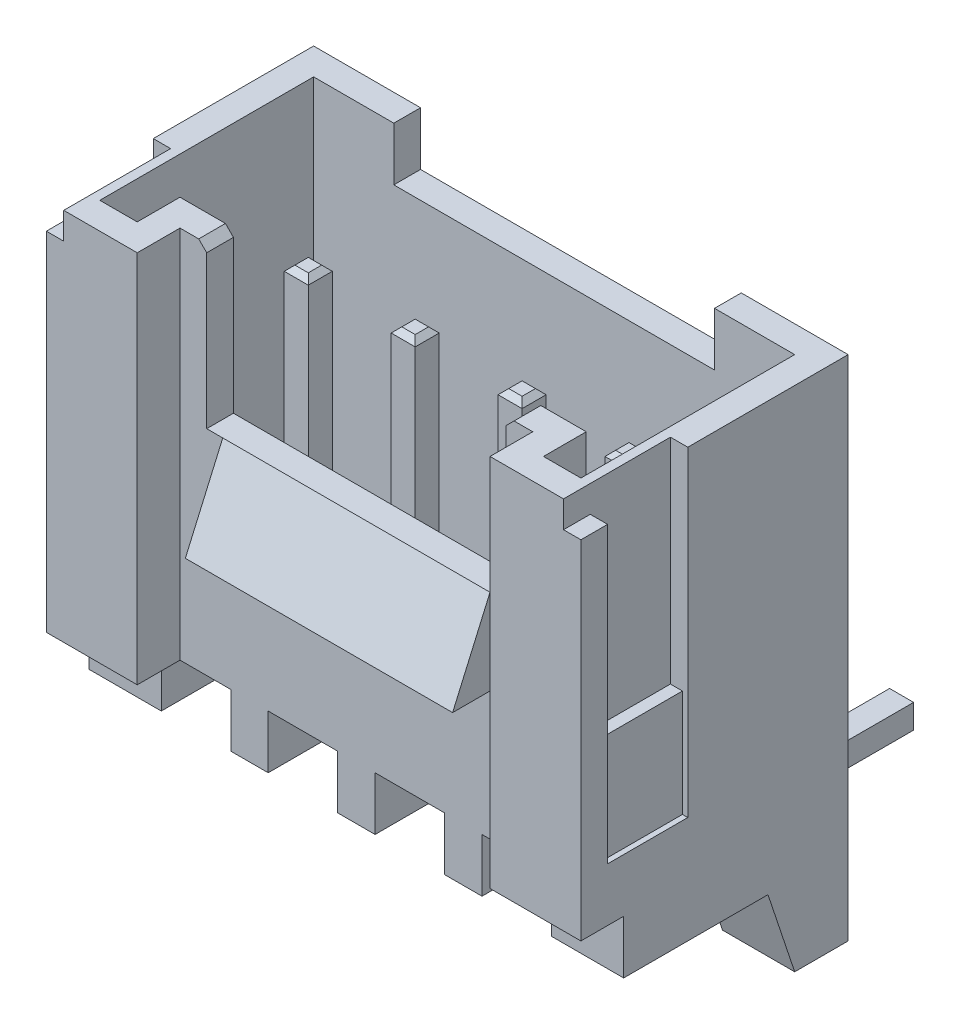
SolidWorks part; units mm, degrees
material "ABS"
ref_plane "Plan de face" through (0, 0, 0) normal (0, 0, 1) x (1, 0, 0)
ref_plane "Plan de dessus" through (0, 0, 0) normal (0, 1, 0) x (1, 0, 0)
ref_plane "Plan de droite" through (0, 0, 0) normal (1, 0, 0) x (0, 0, -1)
sketch "Esquisse1" plane through (0, 0, 0) normal (0, 1, 0) x (1, 0, 0)
  line L1 (-5, 0) -> (5, 0)
  line L2 (-5, 0) -> (-5, 5)
  line L3 (-5, 5) -> (5, 5)
  line L4 (5, 0) -> (5, 5)
  dimension "D1" = 10
  dimension "D2" = 5
extrude "Boss.-Extru.1" add sketch "Esquisse1" along normal blind 8
sketch "Esquisse7" plane through (5, 0, 0) normal (1, 0, 0) x (0, 0, -1)
  line L1 (0, 0) -> (0.8, 0)
  line L2 (0, 0) -> (0, 1)
  line L3 (0, 1) -> (0.8, 1)
  line L4 (0.8, 0) -> (0.8, 1)
  dimension "D1" = 0.8
  dimension "D2" = 1
extrude "Enlèv. mat.-Extru.5" cut sketch "Esquisse7" against normal through all
ref_plane "Plan1" through (3, 0, 0) normal (1, 0, 0) x (0, 0, -1)
sketch "Esquisse8" plane through (3, 0, 0) normal (1, 0, 0) x (0, 0, -1)
  line L0 (0.8, 1) -> (1.1, 1)
  line L1 (1.1, 1) -> (1.9, 0.2)
  line L2 (1.9, 0.2) -> (3.9, 0.2)
  line L3 (3.9, 0.2) -> (4.7, 1)
  line L4 (4.7, 1) -> (5, 1)
  line L5 (5, 8) -> (5, 0) construction
  line L6 (5, 1) -> (5, 0)
  line L7 (5, 0) -> (0.8, 0)
  line L8 (0.8, 0) -> (0.8, 1)
  line L9 (0.8, 0) -> (0.8, 1) construction
  dimension "D1" = 0.2
  dimension "D2" = 0.3
  dimension "D3" = 45
extrude "Enlèv. mat.-Extru.6" cut sketch "Esquisse8" against normal mid plane 1.3
pattern_linear "Répétition linéaire3" count 4 spacing 2 along (-1, 0, 0) of "Enlèv. mat.-Extru.6"
sketch "Esquisse2" plane through (0, 8, 0) normal (0, 1, 0) x (1, 0, 0)
  line L0 (-5, 0) -> (5, 0) construction
  line L1 (-3.3, -0.8) -> (3.3, -0.8)
  line L2 (-3.3, -0.8) -> (-3.3, 0.8)
  line L3 (-3.3, 0.8) -> (3.3, 0.8)
  line L4 (3.3, -0.8) -> (3.3, 0.8)
  line L5 (-3.3, -0.8) -> (3.3, 0.8) construction
  line L6 (-3.3, 0.8) -> (3.3, -0.8) construction
  line L7 (5, 0) -> (5, 5) construction
  point P0 (0, 0)
  dimension "D1" = 0.8
  dimension "D2" = 1.7
extrude "Enlèv. mat.-Extru.1" cut sketch "Esquisse2" against normal through all
sketch "Esquisse4" plane through (0, 8, 0) normal (0, 1, 0) x (1, 0, 0)
  line L16 (-3.8, 1.3) -> (3.8, 1.3)
  line L17 (3.8, 1.3) -> (3.8, 0.5)
  line L18 (3.8, 0.5) -> (4.5, 0.5)
  line L19 (4.5, 0.5) -> (4.5, 4.5)
  line L20 (4.5, 4.5) -> (-4.5, 4.5)
  line L21 (-4.5, 4.5) -> (-4.5, 0.5)
  line L22 (-4.5, 0.5) -> (-3.8, 0.5)
  line L23 (-3.8, 0.5) -> (-3.8, 1.3)
  line L24 (-3.8, 1.3) -> (3.8, 1.3)
  line L25 (3.8, 1.3) -> (3.8, 0.5)
  line L26 (3.8, 0.5) -> (4.5, 0.5)
  line L27 (4.5, 0.5) -> (4.5, 4.5)
  line L28 (4.5, 4.5) -> (-4.5, 4.5)
  line L29 (-4.5, 4.5) -> (-4.5, 0.5)
  line L30 (-4.5, 0.5) -> (-3.8, 0.5)
  line L31 (-3.8, 0.5) -> (-3.8, 1.3)
  dimension "D1" = 0.5
extrude "Enlèv. mat.-Extru.2" cut sketch "Esquisse4" against normal blind 6.5
sketch "Esquisse5" plane through (0, 8, 0) normal (0, 1, 0) x (1, 0, 0)
  line L0 (4.5, 4.5) -> (-4.5, 4.5) construction
  line L1 (-3, 4) -> (3, 4)
  line L2 (-3, 4) -> (-3, 5)
  line L3 (-3, 5) -> (3, 5)
  line L4 (3, 4) -> (3, 5)
  line L5 (-3, 4) -> (3, 5) construction
  line L6 (-3, 5) -> (3, 4) construction
  line L7 (5, 5) -> (-5, 5) construction
  line L8 (5, 0) -> (5, 5) construction
  point P0 (0, 4.5)
  dimension "D1" = 2
extrude "Enlèv. mat.-Extru.3" cut sketch "Esquisse5" against normal blind 1
sketch "Esquisse6" plane through (0, 8, 0) normal (0, 1, 0) x (1, 0, 0)
  line L0 (3.3, 0.8) -> (-3.3, 0.8) construction
  line L1 (-2.8, 0.3) -> (2.8, 0.3)
  line L2 (-2.8, 0.3) -> (-2.8, 1.3)
  line L3 (-2.8, 1.3) -> (2.8, 1.3)
  line L4 (2.8, 0.3) -> (2.8, 1.3)
  line L5 (-2.8, 0.3) -> (2.8, 1.3) construction
  line L6 (-2.8, 1.3) -> (2.8, 0.3) construction
  line L7 (-3.8, 1.3) -> (3.8, 1.3) construction
  line L8 (5, 0) -> (5, 5) construction
  point P0 (0, 0.8)
  dimension "D1" = 2.2
extrude "Enlèv. mat.-Extru.4" cut sketch "Esquisse6" against normal blind 3
sketch "Esquisse11" plane through (0, 0, 0) normal (1, 0, 0) x (0, 0, -1)
  line L0 (0.8, 5) -> (0.1, 3.4)
  line L1 (0.8, 5) -> (0.8, 8) construction
  line L2 (1.3, 5) -> (0.8, 5) construction
  line L3 (0.1, 3.4) -> (0.8, 3.4)
  line L4 (0.8, 1) -> (0.8, 8) construction
  line L5 (0.8, 3.4) -> (0.8, 5)
  dimension "D1" = 0.7
  dimension "D2" = 1.6
extrude "Boss.-Extru.2" add sketch "Esquisse11" along normal mid plane 5
chamfer "Chanfrein1" distance 0.15 angle 45 2 edges at (2.8, 8, -1.05) (-2.8, 8, -1.05)
sketch "Esquisse16" plane through (3, 0, 0) normal (-1, 0, 0) x (0, 0, 1)
  line L0 (-2.9, 6.5) -> (-2.9, -0.0271)
  line L2 (-3.9, 0.2) -> (-1.9, 0.2) construction
  line L3 (-5, 8) -> (-5, 0) construction
  line L5 (-3.076, -0.2467) -> (-8, -0.2467)
  line L7 (-5, 0) -> (-0.8, 0) construction
  arc A1 (-2.9, -0.0271) -> (-3.076, -0.2467) centre (-3.125, -0.0271) cw
  point P2 (-2.9, 0.2)
  point P13 (-4.775, -0.7)
  point P16 (-2.9, -0.2)
  dimension "D4" = 0.5
  dimension "D1" = 0.4
  dimension "D2" = 6.3
  dimension "D3" = 3
  dimension "D5" = 0.2467
extrude "Extru.-Mince2" add sketch "Esquisse16" along normal mid plane 0.45 separate body thin
ref_plane "Plan2" through (0, -1.6, 0) normal (0, -1, 0) x (-1, 0, 0)
pattern_linear "Répétition linéaire4" count 4 spacing 2 along (-1, 0, 0) of bodies 112 114
sketch "Esquisse18" plane through (-5, 0, 0) normal (-1, 0, 0) x (0, 0, 1)
  line L0 (-5, 0) -> (-5, -1.5)
  line L1 (-5, -1.5) -> (-4, -1.5)
  line L2 (-4, -1.5) -> (-3.5, 0)
  line L3 (-5, 0) -> (-0.8, 0) construction
  line L4 (-3.5, 0) -> (-5, 0)
  dimension "D1" = 1.5
  dimension "D2" = 1.5
  dimension "D3" = 1
extrude "Boss.-Extru.4" add sketch "Esquisse18" against normal blind 1.35
chamfer "Chanfrein2" distance 0.1 angle 45 4 edges at (3, 6.5, -2.675) (2.775, 6.5, -2.9) (3, 6.5, -3.125) (3.225, 6.5, -2.9)
sketch "Esquisse19" plane through (-5, 0, 0) normal (-1, 0, 0) x (0, 0, 1)
  line L0 (-3.5, 0) -> (-0.8, 0) construction
  line L1 (-2, 8.4401) -> (-0.5, 8.4401)
  line L2 (-2, 8.4401) -> (-2, 2)
  line L3 (-2, 2) -> (-0.5, 2)
  line L4 (-0.5, 8.4401) -> (-0.5, 2)
  line L5 (0, 8) -> (0, 1) construction
  dimension "D1" = 2
  dimension "D2" = 0.5
  dimension "D3" = 1.5
extrude "Enlèv. mat.-Extru.7" cut sketch "Esquisse19" against normal blind 0.1
sketch "Esquisse20" plane through (-4.9, 0, 0) normal (-1, 0, 0) x (0, 0, 1)
  line L0 (-2, 8) -> (-2, 2) construction
  line L1 (-2, 4) -> (-0.5, 4)
  line L2 (-2, 4) -> (-2, 8.3888)
  line L3 (-2, 8.3888) -> (0.5607, 8.3888)
  line L4 (-0.5, 4) -> (-0.5, 7.5)
  line L5 (-0.5, 2) -> (-0.5, 8) construction
  line L6 (-2, 2) -> (-0.5, 2) construction
  line L7 (-0.5, 7.5) -> (0.5607, 7.5)
  line L8 (0.5607, 7.5) -> (0.5607, 8.3888)
  line L9 (-0.5, 8) -> (0, 8) construction
  dimension "D1" = 2
  dimension "D2" = 0.5
extrude "Enlèv. mat.-Extru.8" cut sketch "Esquisse20" against normal blind 0.225 and the other way blind 0.225
mirror "Symétrie5" about plane through (0, 0, 0) normal (1, 0, 0) of "Enlèv. mat.-Extru.7"
mirror "Symétrie6" about plane through (0, 0, 0) normal (1, 0, 0) of "Enlèv. mat.-Extru.8"
chamfer "Chanfrein3" distance 0.1 angle 45 4 edges at (-3, 6.5, -2.675) (-3.225, 6.5, -2.9) (-3, 6.5, -3.125) (-2.775, 6.5, -2.9)
chamfer "Chanfrein4" distance 0.1 angle 45 4 edges at (-1, 6.5, -2.675) (-1.225, 6.5, -2.9) (-1, 6.5, -3.125) (-0.775, 6.5, -2.9)
chamfer "Chanfrein5" distance 0.1 angle 45 4 edges at (1, 6.5, -2.675) (0.775, 6.5, -2.9) (1, 6.5, -3.125) (1.225, 6.5, -2.9)
mirror "Symétrie8" about plane through (0, 0, 0) normal (1, 0, 0) of "Boss.-Extru.4"
